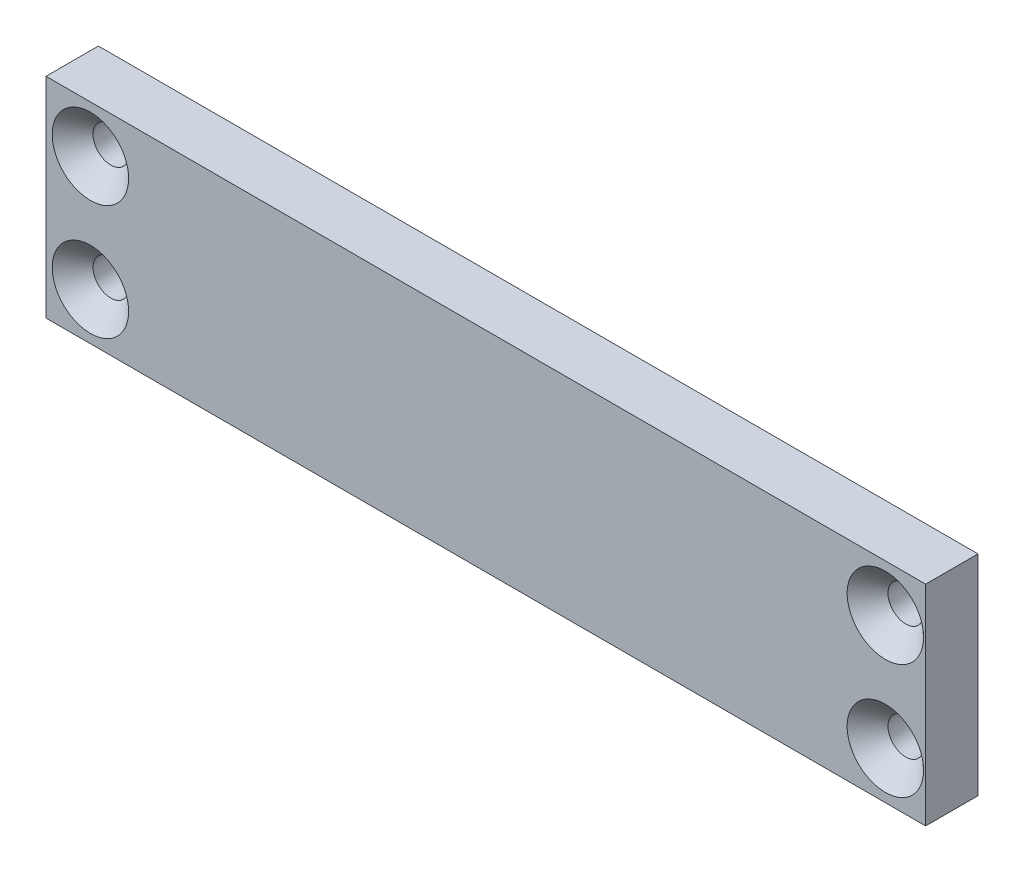
SolidWorks part; units mm, degrees
ref_plane "Front Plane" through (0, 0, 0) normal (0, 0, 1) x (1, 0, 0)
ref_plane "Top Plane" through (0, 0, 0) normal (0, 1, 0) x (1, 0, 0)
ref_plane "Right Plane" through (0, 0, 0) normal (1, 0, 0) x (0, 0, -1)
sketch "Sketch1" plane through (0, 0, 0) normal (0, 0, 1) x (1, 0, 0)
  line L1 (-42, 10) -> (42, 10)
  line L2 (-42, 10) -> (-42, -10)
  line L3 (-42, -10) -> (42, -10)
  line L4 (42, 10) -> (42, -10)
  line L5 (-42, 10) -> (42, -10) construction
  line L6 (-42, -10) -> (42, 10) construction
  point P0 (0, 0)
  dimension "D1" = 84
  dimension "D2" = 20
extrude "Boss-Extrude1" add sketch "Sketch1" along normal blind 5 contours L1 L4 L3 L2
sketch "Sketch2" plane through (0, 0, 5) normal (0, 0, 1) x (1, 0, 0)
  circle A0 centre (38.1537, 5.5) radius 2
  circle A1 centre (38.1537, -5.5) radius 2
  circle A2 centre (-37.7584, 5.5) radius 2
  circle A3 centre (-37.7584, -5.5) radius 2
  point P0 (38.1537, 5.5)
  point P3 (38.1537, -5.5)
  point P6 (-37.7584, 5.5)
  point P9 (-37.7584, -5.5)
hole_wizard "CSK for M3 Flat Head Machine Screw1" positions "Sketch2" profile "Sketch3" countersink size "M3" standard "ANSI Metric"
sketch "Sketch3" plane through (38.1537, 5.5, 5) normal (1, 0, 0) x (0, -1, 0)
  line L0 (0, 0) -> (0, 13.0215)
  line L1 (0, 13.0215) -> (1.7, 12)
  line L2 (1.7, 12) -> (1.7, 1.95)
  line L3 (1.7, 1.95) -> (3.65, 0)
  line L5 (3.65, 0) -> (0, 0)
  line L6 (-1.7, 1.95) -> (-3.65, 0) construction
  line L10 (0, 13.0215) -> (-1.7, 12) construction
  line L11 (0, -6.35) -> (0, 107.95) construction
  dimension "Hole Dia." = 3.4
  dimension "Hole Depth" = 12
  dimension "Near C'Sink Dia." = 7.3
  dimension "Near C'Sink Angle" = 90
  dimension "Drill Angle" = 118
